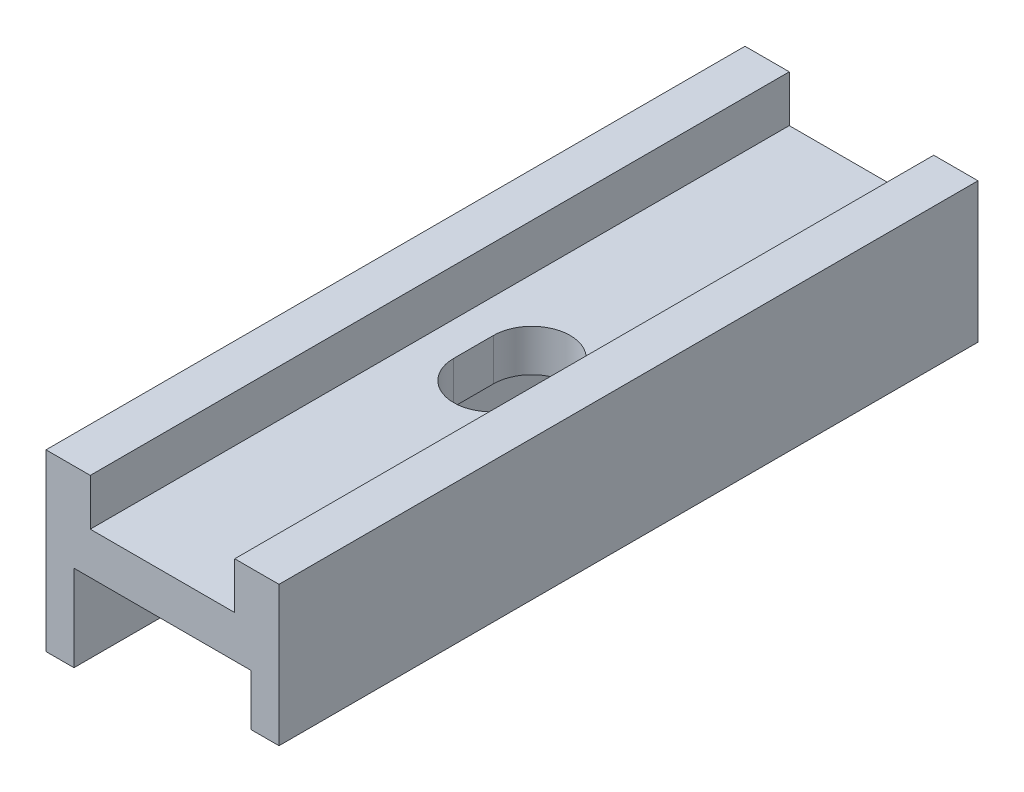
SolidWorks part; units mm, degrees
ref_plane "Front" through (0, 0, 0) normal (0, 0, 1) x (1, 0, 0)
ref_plane "Top" through (0, 0, 0) normal (0, 1, 0) x (1, 0, 0)
ref_plane "Right" through (0, 0, 0) normal (1, 0, 0) x (0, 0, -1)
sketch "Sketch1" plane through (0, 0, 0) normal (0, 0, 1) x (1, 0, 0)
  line L0 (-12.7, 7.62) -> (-7.874, 7.62)
  line L1 (-7.874, 7.62) -> (-7.874, 2.54)
  line L2 (-7.874, 2.54) -> (7.874, 2.54)
  line L3 (7.874, 2.54) -> (7.874, 7.62)
  line L4 (7.874, 7.62) -> (12.7, 7.62)
  line L5 (12.7, 7.62) -> (12.7, -7.62)
  line L6 (12.7, -7.62) -> (9.652, -7.62)
  line L7 (9.652, -7.62) -> (9.652, -2.032)
  line L8 (9.652, -2.032) -> (-9.652, -2.032)
  line L9 (-9.652, -2.032) -> (-9.652, -11.43)
  line L10 (-9.652, -11.43) -> (-12.7, -11.43)
  line L11 (-12.7, -11.43) -> (-12.7, 7.62)
  line L12 (0, -50) -> (0, 50) construction
  line L13 (50, 0) -> (-50, 0) construction
  point P12 (0, 2.54)
  point P15 (12.7, 0)
  point P18 (11.176, -7.62)
  dimension "D1" = 4.826
  dimension "D2" = 3.048
  dimension "D3" = 25.4
  dimension "D4" = 15.24
  dimension "D5" = 19.05
  dimension "D6" = 4.572
  dimension "D7" = 5.08
extrude "Boss-Extrude1" add sketch "Sketch1" along normal mid plane 76.2 contours L4 L5 L6 L7 L8 L9 L10 L11 L0 L1 L2 L3
sketch "Sketch2" plane through (0, 2.54, 0) normal (0, 1, 0) x (1, 0, 0)
  line L0 (0, 2.159) -> (0, -2.159) construction
  line L1 (0, -50) -> (0, 50) construction
  line L2 (4.191, 2.159) -> (4.191, -2.159)
  line L3 (-4.191, 2.159) -> (-4.191, -2.159)
  line L4 (-7.874, 38.1) -> (7.874, 38.1) construction
  line L5 (-7.874, -38.1) -> (7.874, -38.1) construction
  arc A0 (4.191, 2.159) -> (-4.191, 2.159) centre (0, 2.159) ccw
  arc A1 (-4.191, -2.159) -> (4.191, -2.159) centre (0, -2.159) ccw
  point P5 (0, 0)
  point P12 (0, 6.35)
  point P13 (0, -6.35)
  dimension "D1" = 31.75
  dimension "D2" = 31.75
  dimension "D3" = 8.382
extrude "Cut-Extrude1" cut sketch "Sketch2" against normal up to next contours A1 L2 A0 L3
